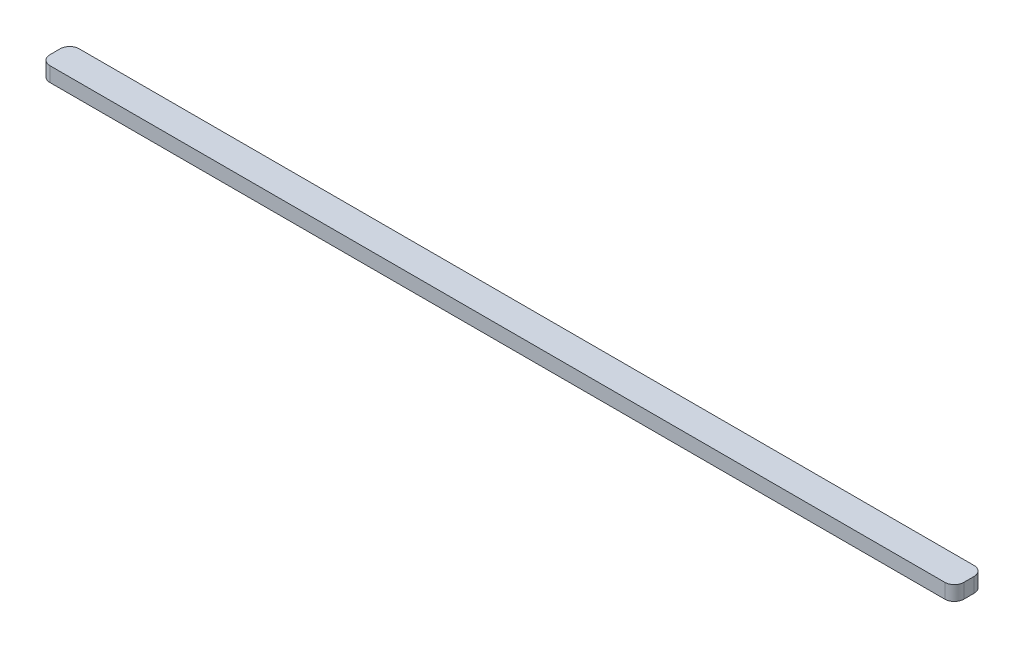
SolidWorks part; units mm, degrees
ref_plane "Alzado" through (0, 0, 0) normal (0, 0, 1) x (1, 0, 0)
ref_plane "Planta" through (0, 0, 0) normal (0, 1, 0) x (1, 0, 0)
ref_plane "Vista lateral" through (0, 0, 0) normal (1, 0, 0) x (0, 0, -1)
sketch "Croquis1" plane through (0, 0, 0) normal (0, 1, 0) x (1, 0, 0)
  line L0 (-61.2, 0) -> (61.2, 0)
  line L1 (-62.5, 1.3) -> (-62.5, 2.7)
  line L2 (-61.2, 4) -> (61.2, 4)
  line L3 (62.5, 2.7) -> (62.5, 1.3)
  line L14 (0, 0) -> (0, -61.4623) construction
  arc A0 (62.5, 2.7) -> (61.2, 4) centre (61.2, 2.7) ccw
  arc A1 (62.5, 1.3) -> (61.2, 0) centre (61.2, 1.3) cw
  arc A2 (-62.5, 2.7) -> (-61.2, 4) centre (-61.2, 2.7) cw
  arc A3 (-62.5, 1.3) -> (-61.2, 0) centre (-61.2, 1.3) ccw
  point P5 (0, 0)
  point P10 (62.5, 0)
  point P13 (-62.5, 4)
  point P16 (-62.5, 0)
  point P41 (-65.601, -56.5385)
  point P42 (-66.0445, -56.982)
  dimension "D3" = 1.3
  dimension "D1" = 125
  dimension "D2" = 4
extrude "Saliente-Extruir1" add sketch "Croquis1" along normal blind 2
